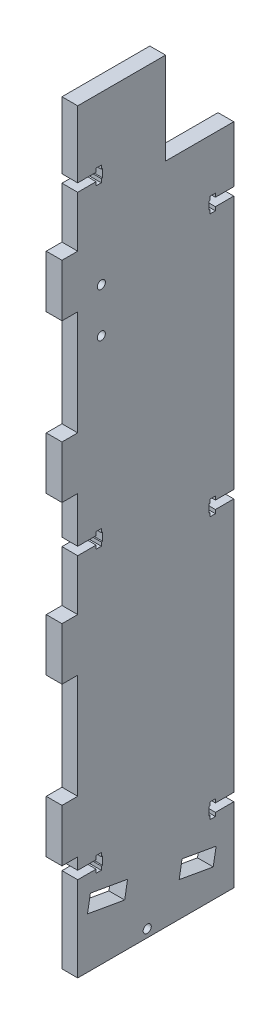
SolidWorks part; units mm, degrees
ref_plane "Płaszczyzna przednia" through (0, 0, 0) normal (0, 0, 1) x (1, 0, 0)
ref_plane "Płaszczyzna górna" through (0, 0, 0) normal (0, 1, 0) x (1, 0, 0)
ref_plane "Płaszczyzna prawa" through (0, 0, 0) normal (1, 0, 0) x (0, 0, -1)
sketch "Szkic1" plane through (0, 0, 0) normal (0, 0, 1) x (1, 0, 0)
  line L0 (-110, -166.604) -> (-110, -484.604)
  line L2 (-110, -484.604) -> (-104, -484.604)
  line L3 (-104, -166.604) -> (-104, -484.604)
  line L4 (-110, -166.604) -> (-104, -166.604)
  dimension "D1" = 6
  dimension "D2" = 318
extrude "Dodanie-wyciągnięcie1" add sketch "Szkic1" along normal blind 65 and the other way blind 6.5
sketch "Szkic2" plane through (-110, 0, 0) normal (-1, 0, 0) x (0, 0, 1)
  line L0 (-6.5, -231.604) -> (25.5, -231.604)
  line L1 (-6.5, -231.604) -> (-6.5, -166.604)
  line L2 (25.5, -231.604) -> (25.5, -196.604)
  line L3 (-6.5, -166.604) -> (65, -166.604)
  line L4 (-6.5, -166.604) -> (-6.5, -484.604) construction
  line L5 (-6.5, -166.604) -> (65, -166.604) construction
  line L9 (25.5, -196.604) -> (65, -196.604)
  line L10 (65, -166.604) -> (65, -196.604)
  line L11 (65, -166.604) -> (65, -484.604) construction
  dimension "D1" = 30
  dimension "D2" = 32
  dimension "D3" = 65
  dimension "D4" = 0
  dimension "D5" = 0
extrude "Wytnij-wyciągnięcie1" cut sketch "Szkic2" against normal blind 6
sketch "Szkic4" plane through (-110, 0, 0) normal (-1, 0, 0) x (0, 0, 1)
  line L0 (-6.5, -484.604) -> (-6.5, -231.604)
  line L1 (-6.5, -484.604) -> (-0.5, -484.604)
  line L2 (-6.5, -231.604) -> (-0.5, -231.604)
  line L3 (-0.5, -484.604) -> (-0.5, -231.604)
  line L4 (-6.5, -231.604) -> (-6.5, -484.604) construction
  line L6 (-6.5, -231.604) -> (25.5, -231.604) construction
  dimension "D1" = 6
  dimension "D2" = 0
extrude "Wytnij-wyciągnięcie2" cut sketch "Szkic4" against normal blind 6
sketch "Szkic5" plane through (-110, 0, 0) normal (-1, 0, 0) x (0, 0, 1)
  line L0 (-0.5, -453.054) -> (-0.5, -456.154)
  line L1 (-0.5, -453.054) -> (6.5, -453.054)
  line L2 (-0.5, -456.154) -> (6.5, -456.154)
  line L3 (9, -453.054) -> (9, -456.154)
  line L4 (-0.5, -484.604) -> (-0.5, -231.604) construction
  line L5 (6.5, -451.679) -> (8.5, -451.679)
  line L6 (6.5, -451.679) -> (6.5, -453.054)
  line L7 (8.5, -451.679) -> (8.5, -453.054)
  line L8 (6.5, -457.529) -> (8.5, -457.529)
  line L9 (6.5, -456.154) -> (6.5, -457.529)
  line L10 (8.5, -453.054) -> (9, -453.054)
  line L11 (8.5, -456.154) -> (8.5, -457.529)
  line L12 (8.5, -456.154) -> (9, -456.154)
  line L15 (-0.5, -484.604) -> (65, -484.604) construction
  point P14 (-0.5, -454.604)
  dimension "D1" = 3.1
  dimension "D2" = 5.85
  dimension "D3" = 1.375
  dimension "D4" = 2
  dimension "D5" = 0.5
  dimension "D6" = 9.5
  dimension "D7" = 30
extrude "Wytnij-wyciągnięcie3" cut sketch "Szkic5" against normal blind 6
pattern_linear "Szyk liniowy2" count 2 spacing 100 along (0, 1, 0) count 2 spacing 200 along (0, 1, 0) of "Wytnij-wyciągnięcie3"
sketch "Szkic6" plane through (-104, 0, 0) normal (1, 0, 0) x (0, 0, -1)
  line L0 (-65, -484.604) -> (-65, -444.604)
  line L1 (-65, -484.604) -> (-59, -484.604)
  line L2 (-65, -444.604) -> (-59, -444.604)
  line L3 (-59, -484.604) -> (-59, -444.604)
  line L4 (-65, -484.604) -> (-65, -196.604) construction
  dimension "D1" = 6
  dimension "D2" = 40
extrude "Wytnij-wyciągnięcie4" cut sketch "Szkic6" against normal blind 6
pattern_linear "Szyk liniowy3" count 6 spacing 60 along (0, 1, 0) count 2 spacing 250 along (0, 1, 0) of "Wytnij-wyciągnięcie4"
sketch "Szkic7" plane through (-104, 0, 0) normal (1, 0, 0) x (0, 0, -1)
  line L0 (-59, -449.054) -> (-59, -452.154)
  line L1 (-59, -449.054) -> (-52, -449.054)
  line L2 (-59, -452.154) -> (-52, -452.154)
  line L3 (-49.5, -449.054) -> (-49.5, -452.154)
  line L4 (-59, -484.604) -> (-59, -444.604) construction
  line L5 (-52, -447.679) -> (-50, -447.679)
  line L6 (-52, -447.679) -> (-52, -449.054)
  line L7 (-50, -447.679) -> (-50, -449.054)
  line L8 (-52, -453.529) -> (-50, -453.529)
  line L9 (-50, -449.054) -> (-49.5, -449.054)
  line L10 (-52, -452.154) -> (-52, -453.529)
  line L11 (-50, -452.154) -> (-50, -453.529)
  line L12 (-50, -452.154) -> (-49.5, -452.154)
  line L13 (0.5, -484.604) -> (-59, -484.604) construction
  point P14 (-59, -450.604)
  dimension "D1" = 3.1
  dimension "D2" = 0.5
  dimension "D3" = 2
  dimension "D4" = 1.375
  dimension "D5" = 5.85
  dimension "D6" = 34
  dimension "D7" = 9.5
extrude "Wytnij-wyciągnięcie5" cut sketch "Szkic7" against normal blind 6
pattern_linear "Szyk liniowy4" count 2 spacing 107 along (0, 1, 0) count 2 spacing 227 along (0, 1, 0) of "Wytnij-wyciągnięcie5"
sketch "Szkic8" plane through (-110, 0, 0) normal (-1, 0, 0) x (0, 0, 1)
  line L0 (34.05, -484.604) -> (34.05, -478.604) construction
  line L1 (30.95, -484.604) -> (30.95, -478.604) construction
  line L2 (34.05, -484.604) -> (34.05, -478.604)
  line L3 (30.95, -484.604) -> (30.95, -478.604)
  line L4 (30.95, -481.604) -> (34.05, -481.604)
  circle A0 centre (32.5, -481.604) radius 1.55
  dimension "D1" = 3.1
sketch "Szkic9" plane through (-110, 0, 0) normal (-1, 0, 0) x (0, 0, 1)
  circle A0 centre (32.5, -481.604) radius 1.55 construction
  circle A1 centre (32.5, -481.604) radius 1.55
extrude "Wytnij-wyciągnięcie6" cut sketch "Szkic9" against normal blind 6
sketch "Szkic10" plane through (-104, 0, 0) normal (1, 0, 0) x (0, 0, -1)
  line L0 (-20.0849, -471.3034) -> (-19.043, -465.3945) construction
  line L1 (-19.043, -465.3945) -> (-6.4514, -467.6148) construction
  line L2 (-40.2164, -461.6611) -> (-54.0037, -459.23) construction
  line L3 (-20.0849, -471.3034) -> (-7.4933, -473.5236) construction
  line L5 (-55.0456, -465.1389) -> (-54.0037, -459.23) construction
  line L8 (-20.0849, -471.3034) -> (-19.043, -465.3945)
  line L9 (-19.043, -465.3945) -> (-6.4514, -467.6148)
  line L10 (-7.4933, -473.5236) -> (-6.4514, -467.6148)
  line L11 (-20.0849, -471.3034) -> (-7.4933, -473.5236)
  line L12 (-41.2583, -467.5699) -> (-55.0456, -465.1389) construction
  line L13 (-55.0456, -465.1389) -> (-54.0037, -459.23)
  line L14 (-41.2583, -467.5699) -> (-40.2164, -461.6611) construction
  line L15 (-40.2164, -461.6611) -> (-54.0037, -459.23)
  line L16 (-20.3166, -471.4656) -> (-19.2052, -465.1628)
  line L17 (-19.2052, -465.1628) -> (-6.2198, -467.4525)
  line L18 (-7.3311, -473.7553) -> (-6.2198, -467.4525)
  line L19 (-20.3166, -471.4656) -> (-7.3311, -473.7553)
  line L24 (-39.9847, -461.4988) -> (-54.1659, -458.9983)
  line L25 (-55.2773, -465.3011) -> (-54.1659, -458.9983)
  line L26 (-41.096, -467.8016) -> (-55.2773, -465.3011)
  line L27 (-41.2583, -467.5699) -> (-55.0456, -465.1389)
  line L28 (-41.2583, -467.5699) -> (-40.2164, -461.6611)
  line L29 (-41.096, -467.8016) -> (-39.9847, -461.4988)
  dimension "D1" = 0.2
  dimension "D2" = 0.2
sketch "Szkic11" plane through (-104, 0, 0) normal (1, 0, 0) x (0, 0, -1)
  line L0 (-19.2052, -465.1628) -> (-6.2198, -467.4525) construction
  line L1 (-7.3311, -473.7553) -> (-6.2198, -467.4525) construction
  line L2 (-20.3166, -471.4656) -> (-7.3311, -473.7553) construction
  line L3 (-20.3166, -471.4656) -> (-19.2052, -465.1628) construction
  line L8 (-19.2052, -465.1628) -> (-6.2198, -467.4525)
  line L9 (-7.3311, -473.7553) -> (-6.2198, -467.4525)
  line L10 (-20.3166, -471.4656) -> (-7.3311, -473.7553)
  line L11 (-20.3166, -471.4656) -> (-19.2052, -465.1628)
  line L12 (-39.9847, -461.4988) -> (-54.1659, -458.9983) construction
  line L13 (-41.096, -467.8016) -> (-39.9847, -461.4988) construction
  line L14 (-41.096, -467.8016) -> (-55.2773, -465.3011) construction
  line L15 (-55.2773, -465.3011) -> (-54.1659, -458.9983) construction
  line L16 (-39.9847, -461.4988) -> (-54.1659, -458.9983)
  line L17 (-41.096, -467.8016) -> (-39.9847, -461.4988)
  line L18 (-41.096, -467.8016) -> (-55.2773, -465.3011)
  line L19 (-55.2773, -465.3011) -> (-54.1659, -458.9983)
extrude "Wytnij-wyciągnięcie7" cut sketch "Szkic11" against normal blind 6
sketch "Szkic13" plane through (-110, 0, 0) normal (-1, 0, 0) x (0, 0, 1)
  circle A0 centre (50, -260.154) radius 1.55 construction
  circle A1 centre (50, -277.054) radius 1.55 construction
  circle A2 centre (50, -260.154) radius 1.55
  circle A3 centre (50, -277.054) radius 1.55
extrude "Wytnij-wyciągnięcie9" cut sketch "Szkic13" against normal blind 10
equation "\"tolerancja_wpusy\"=0.2"
equation "\"dlugosc_wpustu_duzy\"=20"
equation "\"srednica_otworu_M3\"=3.1"
equation "\"szerokosc_nogi_T\"=3.1"
equation "\"dlugosc_T_30\"=11"
equation "\"grubosc_na_nakretke_kwadrat\"=2"
equation "\"szerokosc_na_nakretke_kwadrat\"=5.85"
equation "\"wyokosc_nadstawki_T\"=0.5"
equation "\"dlugosc_T_20_6\"=14"
equation "\"D1@Szkic5\"=\"szerokosc_nogi_T\""
equation "\"D2@Szkic5\"=\"szerokosc_na_nakretke_kwadrat\""
equation "\"D3@Szkic5\"=(\"szerokosc_na_nakretke_kwadrat\"-\"szerokosc_nogi_T\")/2"
equation "\"D4@Szkic5\"=\"grubosc_na_nakretke_kwadrat\""
equation "\"D5@Szkic5\"=\"wyokosc_nadstawki_T\""
equation "\"D1@Szkic7\"=\"szerokosc_nogi_T\""
equation "\"D2@Szkic7\"=\"wyokosc_nadstawki_T\""
equation "\"D3@Szkic7\"=\"grubosc_na_nakretke_kwadrat\""
equation "\"D4@Szkic7\"=(\"szerokosc_na_nakretke_kwadrat\"-\"szerokosc_nogi_T\")/2"
equation "\"D5@Szkic7\"=\"szerokosc_na_nakretke_kwadrat\""
equation "\"D1@Szkic8\"=\"srednica_otworu_M3\""
